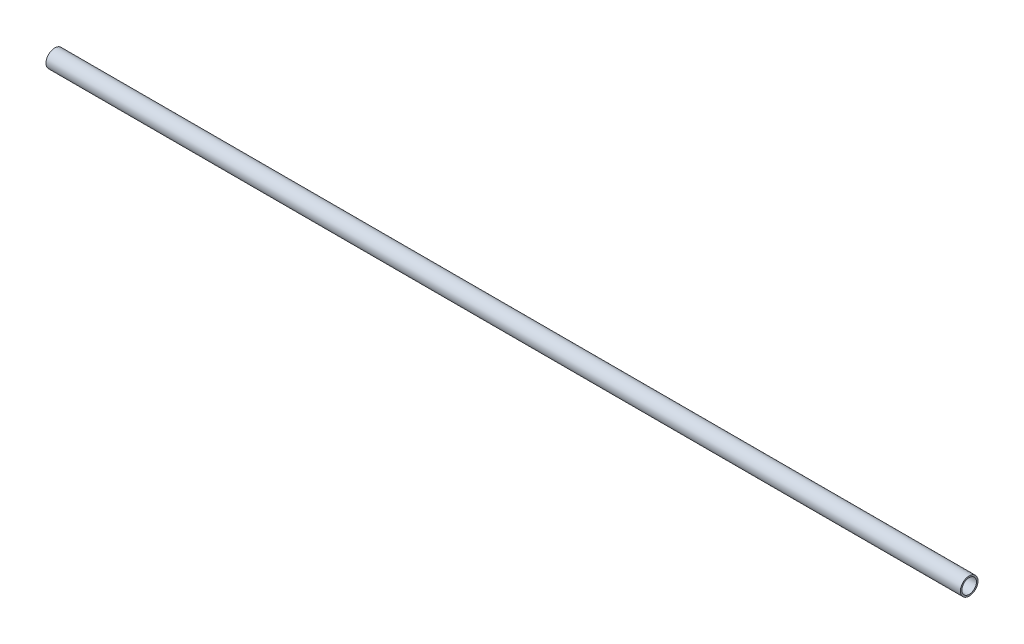
SolidWorks part; units mm, degrees
material "6061-T6 (SS)"
ref_plane "Front Plane" through (0, 0, 0) normal (0, 0, 1) x (1, 0, 0)
ref_plane "Top Plane" through (0, 0, 0) normal (0, 1, 0) x (1, 0, 0)
ref_plane "Right Plane" through (0, 0, 0) normal (1, 0, 0) x (0, 0, -1)
sketch "Sketch1" plane through (0, 0, 0) normal (1, 0, 0) x (0, 0, -1)
  circle A0 centre (0, 0) radius 9.525
  circle A1 centre (0, 0) radius 7.874
  dimension "D1" = 19.05
  dimension "D2" = 15.748
extrude "Boss-Extrude1" add sketch "Sketch1" along normal mid plane 990.6
